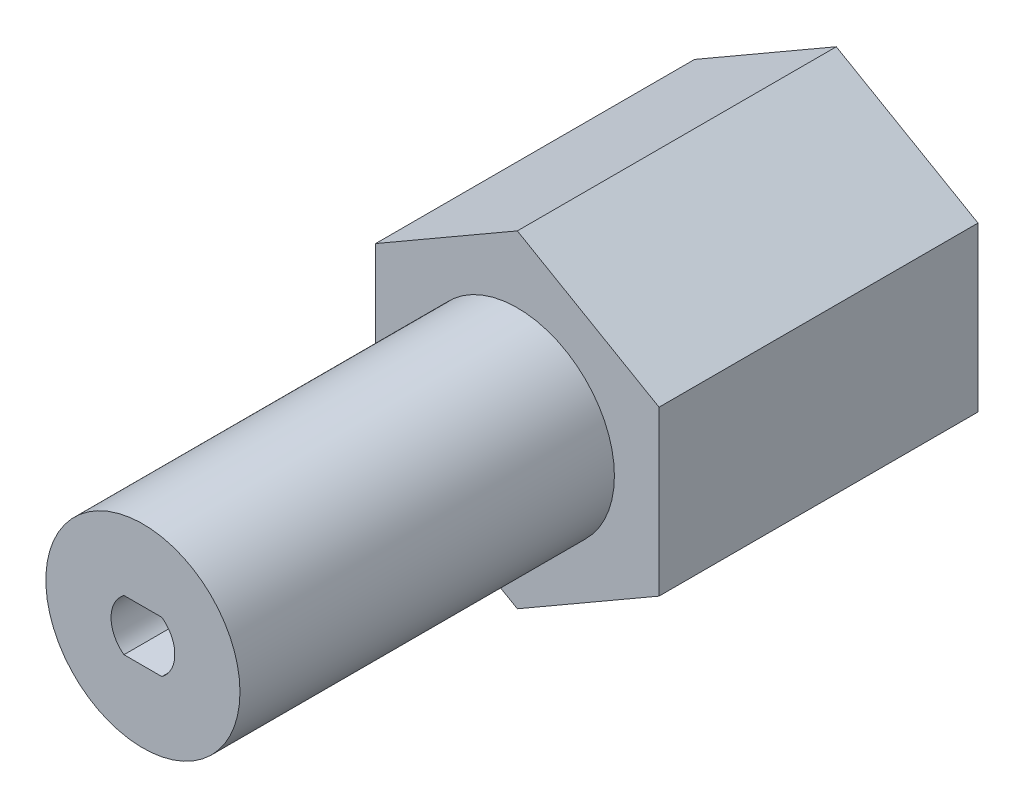
SolidWorks part; units mm, degrees
ref_plane "Front Plane" through (0, 0, 0) normal (0, 0, 1) x (1, 0, 0)
ref_plane "Top Plane" through (0, 0, 0) normal (0, 1, 0) x (1, 0, 0)
ref_plane "Right Plane" through (0, 0, 0) normal (1, 0, 0) x (0, 0, -1)
sketch "Sketch1" plane through (0, 0, 0) normal (0, 0, 1) x (1, 0, 0)
  line L1 (5.1095, -2.95) -> (5.1095, 2.95)
  line L2 (5.1095, 2.95) -> (0, 5.9)
  line L3 (0, 5.9) -> (-5.1095, 2.95)
  line L4 (-5.1095, 2.95) -> (-5.1095, -2.95)
  line L5 (-5.1095, -2.95) -> (0, -5.9)
  line L6 (0, -5.9) -> (5.1095, -2.95)
  circle A0 centre (0, 0) radius 5.1095 construction
  dimension "D1" = 5.9
extrude "Boss-Extrude1" add sketch "Sketch1" along normal blind 11.5
sketch "Sketch2" plane through (0, 0, 11.5) normal (0, 0, 1) x (1, 0, 0)
  circle A0 centre (0, 0) radius 3.5
  dimension "D1" = 7
extrude "Boss-Extrude2" add sketch "Sketch2" along normal blind 13.5
sketch "Sketch4" plane through (0, 0, 25) normal (0, 0, 1) x (1, 0, 0)
  line L0 (-1.3983, 0.925) -> (1.6507, 0.925) construction
  line L1 (-1.3983, -0.925) -> (1.6507, -0.925) construction
  line L2 (0, 0) -> (-2.4005, 0) construction
  line L7 (-0.6833, 0.925) -> (0.6833, 0.925)
  line L8 (-0.6833, -0.925) -> (0.6833, -0.925)
  circle A0 centre (0, 0) radius 1.15 construction
  arc A3 (-0.6833, -0.925) -> (-0.6833, 0.925) centre (0, 0) cw
  arc A4 (0.6833, 0.925) -> (0.6833, -0.925) centre (0, 0) cw
  dimension "D1" = 2.3
  dimension "D2" = 1.85
  dimension "D3" = 0.925
extrude "Cut-Extrude2" cut sketch "Sketch4" against normal through all
